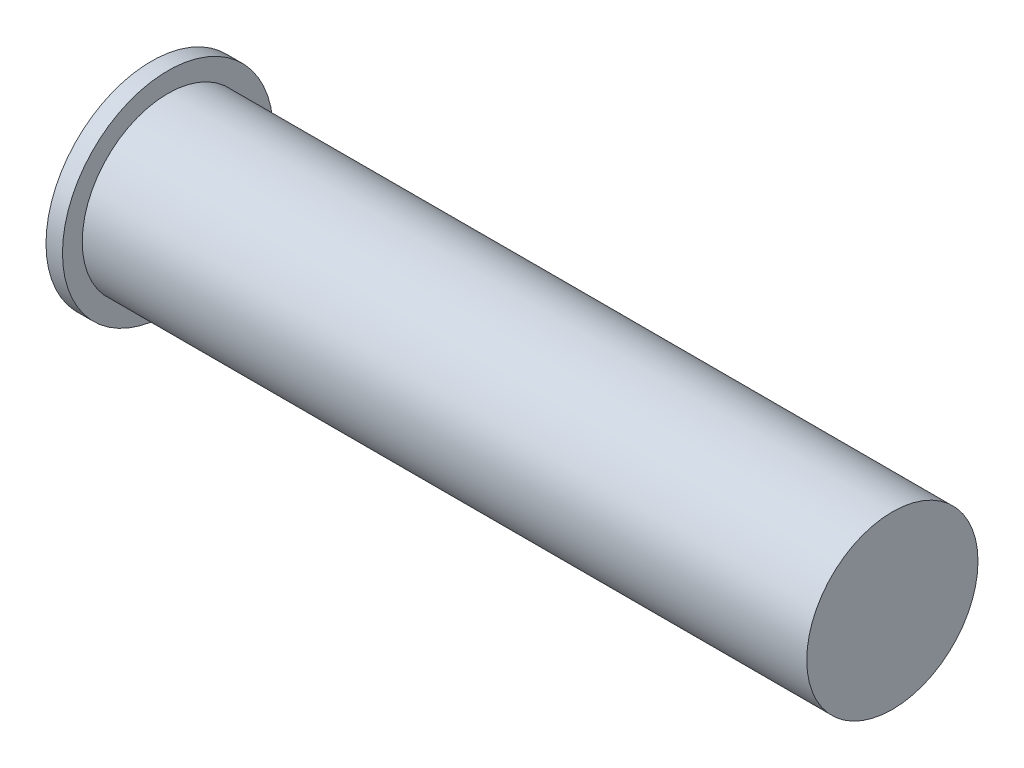
SolidWorks part; units mm, degrees
material "Nickel"
ref_plane "Front Plane" through (0, 0, 0) normal (0, 0, 1) x (1, 0, 0)
ref_plane "Top Plane" through (0, 0, 0) normal (0, 1, 0) x (1, 0, 0)
ref_plane "Right Plane" through (0, 0, 0) normal (1, 0, 0) x (0, 0, -1)
sketch "Sketch1" plane through (0, 0, 0) normal (0, 0, 1) x (1, 0, 0)
  line L0 (0, 0) -> (0, 32)
  line L1 (0, 32) -> (5, 32)
  line L2 (5, 32) -> (5, 26)
  line L3 (5, 26) -> (225, 26)
  line L4 (225, 26) -> (225, 0)
  line L5 (225, 0) -> (0, 0)
  line L6 (0, 0) -> (170.471, 0) construction
  dimension "D1" = 26
  dimension "D2" = 5
  dimension "D3" = 32
  dimension "D4" = 220
revolve "Revolve1" add sketch "Sketch1" angle 360 about L6
sketch "Sketch2" plane through (0, 0, 0) normal (0, 1, 0) x (1, 0, 0)
  line L0 (5, -26) -> (5, 26) construction
  circle A0 centre (105, 28) radius 10
  dimension "D3" = 20
  dimension "D1" = 100
  dimension "D2" = 28
extrude "Cut-Extrude1" cut sketch "Sketch2" against normal through all and the other way through all
